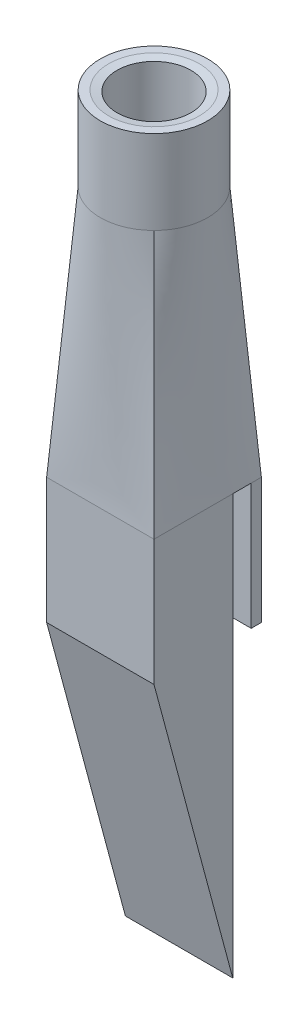
SolidWorks part; units mm, degrees
ref_plane "Front" through (0, 0, 0) normal (0, 0, 1) x (1, 0, 0)
ref_plane "Top" through (0, 0, 0) normal (0, 1, 0) x (1, 0, 0)
ref_plane "Right" through (0, 0, 0) normal (1, 0, 0) x (0, 0, -1)
sketch "Sketch1" plane through (0, 0, 0) normal (0, 1, 0) x (1, 0, 0)
  circle A0 centre (0, 0) radius 4.25 construction
  circle A1 centre (0, 0) radius 4.4
  circle A2 centre (0, 0) radius 6.4
  dimension "D1" = 8.5
  dimension "D3" = 2
  dimension "D2" = 0.15
extrude "Boss-Extrude1" add sketch "Sketch1" along normal blind 10
ref_plane "Plane1" through (0, -30, 0) normal (0, -1, 0) x (-1, 0, 0)
chamfer "Chamfer1" distance 1 angle 10 1 edges at (0, 10, 4.4)
sketch "Sketch2" plane through (0, 0, 0) normal (0, -1, 0) x (1, 0, 0)
  circle A0 centre (0, 0) radius 6.4
  circle A1 centre (0, 0) radius 6.4 construction
sketch "Sketch3" plane through (0, -30, 0) normal (0, -1, 0) x (-1, 0, 0)
  line L1 (6.4, 6.4) -> (-6.4, 6.4)
  line L2 (6.4, 6.4) -> (6.4, -6.4)
  line L3 (6.4, -6.4) -> (-6.4, -6.4)
  line L4 (-6.4, 6.4) -> (-6.4, -6.4)
  line L5 (0, -6.4) -> (0, 6.4) construction
  line L6 (6.4, 0) -> (-6.4, 0) construction
  point P0 (0, 0)
  dimension "D1" = 12.8
  dimension "D2" = 12.8
loft "Loft1" add profiles "Sketch2", "Sketch3"
sketch "Sketch4" plane through (0, 0, 0) normal (0, 1, 0) x (1, 0, 0)
  line L0 (6.4, 5.19) -> (-6.4, 5.19)
  line L1 (6.4, 2.99) -> (-6.4, 2.99)
  line L4 (6.4, -6.4) -> (6.4, 6.4)
  line L5 (-6.4, -6.4) -> (6.4, -6.4)
  line L6 (-6.4, 6.4) -> (-6.4, -6.4)
  line L7 (6.4, 6.4) -> (-6.4, 6.4)
  line L8 (6.4, -6.4) -> (6.4, 6.4)
  line L9 (-6.4, -6.4) -> (6.4, -6.4)
  line L10 (-6.4, 6.4) -> (-6.4, -6.4)
  line L11 (6.4, 6.4) -> (-6.4, 6.4)
  dimension "D2" = 1.21
  dimension "D3" = 2.2
  dimension "D1" = 0
extrude "Boss-Extrude2" add sketch "Sketch4" against normal blind 15 from surface at -30 contours L1 L10 L9 L8 | L8 L11 L10 L0 starting at face at (0, -30, 0)
sketch "Sketch5" plane through (0, 0, 0) normal (1, 0, 0) x (0, 0, -1)
  line L0 (2.99, -45) -> (2.99, -80)
  line L1 (2.99, -80) -> (-6.4, -45)
  line L2 (2.99, -45) -> (-6.4, -45)
  line L3 (2.99, -45) -> (2.99, -30) construction
  dimension "D1" = 35
extrude "Boss-Extrude3" add sketch "Sketch5" along normal up to surface and the other way up to surface up to face at (6.4, -41.25, 2.8788) other way up to face at (-6.4, -41.25, 2.8788)
fillet "Fillet3" [suppressed] radius 10
